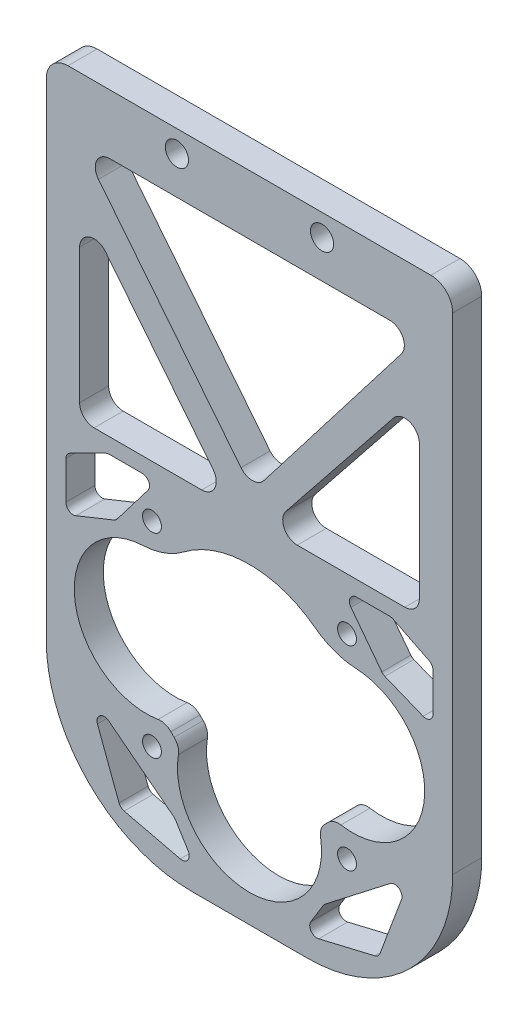
SolidWorks part; units mm, degrees
material "Hexcel AS4C (3000 丝)"
ref_plane "前视基准面" through (0, 0, 0) normal (0, 0, 1) x (1, 0, 0)
ref_plane "上视基准面" through (0, 0, 0) normal (0, 1, 0) x (1, 0, 0)
ref_plane "右视基准面" through (0, 0, 0) normal (1, 0, 0) x (0, 0, -1)
sketch "草图1" plane through (0, 0, 0) normal (0, 0, 1) x (1, 0, 0)
  line L0 (0, 0) -> (0, 45) construction
  line L1 (-28, 45) -> (28, 45)
  line L2 (-28, 45) -> (-28, -45)
  line L3 (-28, -45) -> (28, -45)
  line L4 (28, 45) -> (28, -45)
  line L5 (-28, 45) -> (28, -45) construction
  line L6 (-28, -45) -> (28, 45) construction
  line L7 (0, -17) -> (0, 0) construction
  line L8 (0, -17) -> (19, -17) construction
  line L9 (0, -17) -> (13.435, -3.565) construction
  circle A0 centre (10, 42) radius 1.6
  circle A1 centre (-10, 42) radius 1.6
  circle A2 centre (0, -17) radius 19 construction
  circle A3 centre (13.435, -3.565) radius 1.3
  circle A4 centre (13.435, -30.435) radius 1.3
  circle A5 centre (-13.435, -30.435) radius 1.3
  circle A6 centre (-13.435, -3.565) radius 1.3
  circle A7 centre (0, -17) radius 15
  circle A8 centre (0, -17) radius 28 construction
  point P0 (0, 0)
  point P26 (0, -17)
  dimension "D1" = 3.2
  dimension "D2" = 20
  dimension "D3" = 3
  dimension "D6" = 38
  dimension "D8" = 2.6
  dimension "D10" = 30
  dimension "D11" = 56
  dimension "D4" = 90
  dimension "D5" = 56
  dimension "D7" = 45
  dimension "D9" = 4
extrude "凸台-拉伸1" add sketch "草图1" along normal blind 4
fillet "圆角1" radius 20 2 edges at (28, -45, 2) (-28, -45, 2)
sketch "草图2" plane through (0, 0, 4) normal (0, 0, 1) x (1, 0, 0)
  line L0 (0, -17) -> (0, 45) construction
  line L1 (28, 45) -> (-28, 45) construction
  line L2 (-23.403, 36.7925) -> (23.403, 36.7925)
  line L3 (23.403, 36.7925) -> (0.4261, 6.9639)
  line L4 (0.4261, 6.9639) -> (-23.403, 36.7925)
  line L5 (-23.403, 29.8516) -> (-23.403, 3.5883)
  line L6 (-23.403, 3.5883) -> (-2.422, 3.5883)
  line L7 (-2.422, 3.5883) -> (-23.403, 29.8516)
  line L8 (23.403, 3.5883) -> (2.422, 3.5883)
  line L9 (23.403, 29.8516) -> (23.403, 3.5883)
  line L10 (2.422, 3.5883) -> (23.403, 29.8516)
extrude "切除-拉伸1" cut sketch "草图2" against normal through all
fillet "圆角2" radius 2 9 edges at (23.403, 36.7925, 2) (0.4261, 6.9639, 2) (-23.403, 36.7925, 2) (-23.403, 29.8516, 2) (-2.422, 3.5883, 2) (2.422, 3.5883, 2) (23.403, 29.8516, 2) (23.403, 3.5883, 2) (-23.403, 3.5883, 2)
fillet "圆角3" radius 3 2 edges at (28, 45, 2) (-28, 45, 2)
sketch "草图3" plane through (0, 0, 4) normal (0, 0, 1) x (1, 0, 0)
  line L0 (0, 0) -> (0, -45) construction
  line L1 (-8, -45) -> (8, -45) construction
  arc A0 (-9.5637, -28.5557) -> (9.5637, -28.5557) centre (0, -31.2147) ccw
  arc A1 (-11.5557, -7.4363) -> (-11.5557, -26.5637) centre (0, -17) ccw construction
  arc A2 (-11.5557, -7.4363) -> (-11.5557, -26.5637) centre (-14.2147, -17) ccw
  circle A3 centre (0, -2.7853) radius 9.9265 [skipped]
  arc A4 (11.5557, -26.5637) -> (11.5557, -7.4363) centre (14.2147, -17) ccw
  arc A5 (-9.5637, -28.5557) -> (9.5637, -28.5557) centre (0, -17) ccw construction
  arc A6 (11.5557, -26.5637) -> (11.5557, -7.4363) centre (0, -17) ccw construction
  arc A7 (-11.5557, -7.4363) -> (-11.5557, -26.5637) centre (0, -17) ccw
  arc A8 (11.5557, -26.5637) -> (11.5557, -7.4363) centre (0, -17) ccw
  arc A9 (-9.5637, -28.5557) -> (9.5637, -28.5557) centre (0, -17) ccw
  point P18 (0, -17)
  dimension "D1" = 30
  dimension "D2" = 4
extrude "切除-拉伸2" cut sketch "草图3" against normal through all
fillet "圆角4" radius 10 2 edges at (11.5557, -7.4363, 2) (-11.5557, -7.4363, 2)
fillet "圆角5" radius 2 4 edges at (9.5637, -28.5557, 2) (-9.5637, -28.5557, 2) (11.5557, -26.5637, 2) (-11.5557, -26.5637, 2)
sketch "草图4" plane through (0, 0, 4) normal (0, 0, 1) x (1, 0, 0)
  line L0 (-22.185, -28.2132) -> (-10.2828, -37.4332)
  line L1 (-10.2828, -37.4332) -> (-7.1815, -42.4623)
  line L2 (-7.1815, -42.4623) -> (-17.7864, -39.9477)
  line L3 (-17.7864, -39.9477) -> (-22.185, -28.2132)
  line L4 (0, 0) -> (0, -51.2632) construction
  line L5 (7.1815, -42.4623) -> (17.7864, -39.9477)
  line L6 (10.2828, -37.4332) -> (7.1815, -42.4623)
  line L7 (22.185, -28.2132) -> (10.2828, -37.4332)
  line L8 (17.7864, -39.9477) -> (22.185, -28.2132)
extrude "切除-拉伸3" cut sketch "草图4" against normal through all
fillet "圆角6" radius 1 8 edges at (22.185, -28.2132, 2) (17.7864, -39.9477, 2) (7.1815, -42.4623, 2) (10.2828, -37.4332, 2) (-10.2828, -37.4332, 2) (-7.1815, -42.4623, 2) (-17.7864, -39.9477, 2) (-22.185, -28.2132, 2)
sketch "草图5" plane through (0, 0, 4) normal (0, 0, 1) x (1, 0, 0)
  line L0 (0, 0) -> (0, -18.4478) construction
  line L1 (-19.5729, 1.4762) -> (-25.2954, -1.3851)
  line L2 (-25.2954, -1.3851) -> (-25.2954, -8.7066)
  line L3 (-25.2954, -8.7066) -> (-18.3947, -5.9295)
  line L4 (-18.3947, -5.9295) -> (-12.7564, 1.4762)
  line L5 (-12.7564, 1.4762) -> (-19.5729, 1.4762)
  line L6 (18.3947, -5.9295) -> (12.7564, 1.4762)
  line L7 (25.2954, -8.7066) -> (18.3947, -5.9295)
  line L8 (25.2954, -1.3851) -> (25.2954, -8.7066)
  line L9 (19.5729, 1.4762) -> (25.2954, -1.3851)
  line L10 (12.7564, 1.4762) -> (19.5729, 1.4762)
extrude "切除-拉伸4" cut sketch "草图5" against normal through all
fillet "圆角7" radius 1 10 edges at (12.7564, 1.4762, 2) (19.5729, 1.4762, 2) (25.2954, -1.3851, 2) (25.2954, -8.7066, 2) (18.3947, -5.9295, 2) (-18.3947, -5.9295, 2) (-25.2954, -8.7066, 2) (-25.2954, -1.3851, 2) (-12.7564, 1.4762, 2) (-19.5729, 1.4762, 2)
